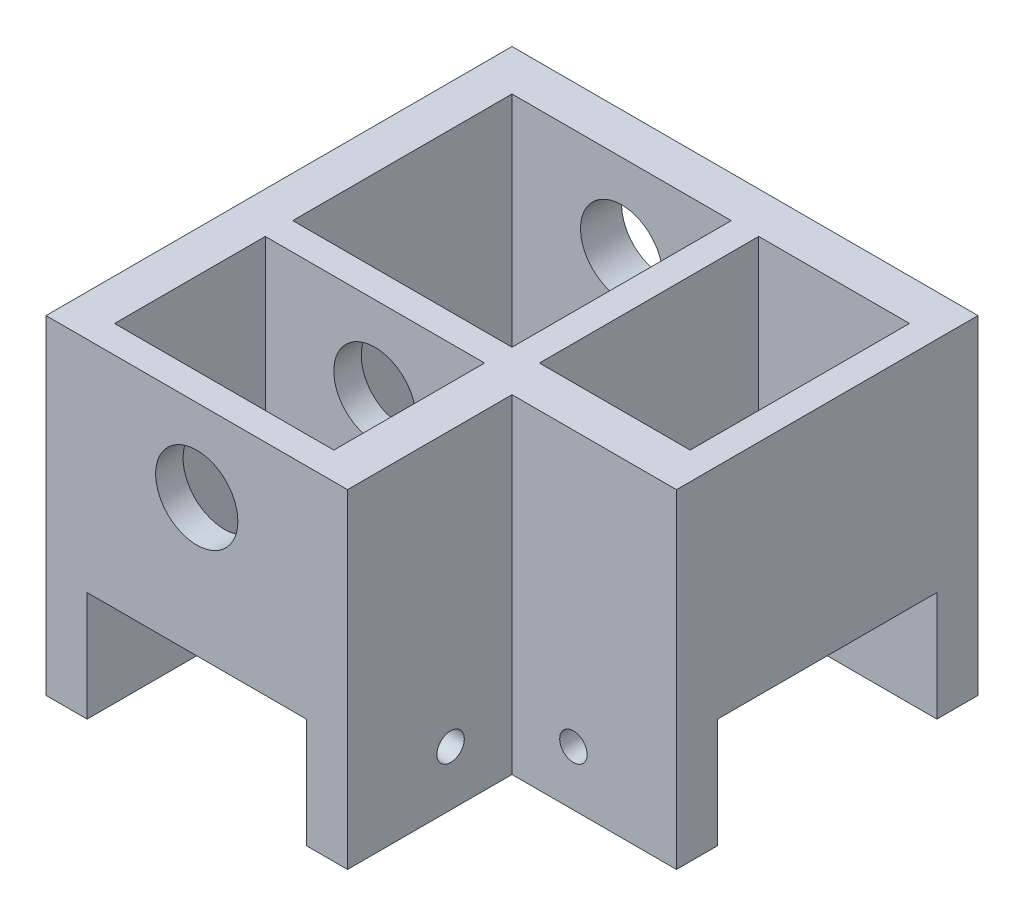
SolidWorks part; units mm, degrees
ref_plane "Front Plane" through (0, 0, 0) normal (0, 0, 1) x (1, 0, 0)
ref_plane "Top Plane" through (0, 0, 0) normal (0, 1, 0) x (1, 0, 0)
ref_plane "Right Plane" through (0, 0, 0) normal (1, 0, 0) x (0, 0, -1)
sketch "Sketch1" plane through (0, 0, 0) normal (0, 1, 0) x (1, 0, 0)
  line L1 (-50.8, -50.8) -> (50.8, -50.8)
  line L2 (-50.8, -50.8) -> (-50.8, 50.8)
  line L3 (-50.8, 50.8) -> (50.8, 50.8)
  line L4 (50.8, -50.8) -> (50.8, 50.8)
  line L5 (-50.8, -50.8) -> (50.8, 50.8) construction
  line L6 (-50.8, 50.8) -> (50.8, -50.8) construction
  point P0 (0, 0)
  dimension "D1" = 101.6
  dimension "D2" = 101.6
extrude "Extrude-Thin1" add sketch "Sketch1" along normal blind 152.4 thin
sketch "Sketch2" plane through (0, 152.4, 0) normal (0, 1, 0) x (1, 0, 0)
  line L0 (-69.85, -69.85) -> (69.85, -69.85) construction
  line L1 (-50.8, -50.8) -> (50.8, -50.8)
  line L2 (-50.8, -50.8) -> (-50.8, -69.85)
  line L3 (-50.8, -69.85) -> (50.8, -69.85)
  line L4 (50.8, -50.8) -> (50.8, -69.85)
ref_plane "Plane1" through (0, 50.8, 0) normal (0, 1, 0) x (1, 0, 0)
sketch "Sketch3" plane through (0, 0, 0) normal (0, -1, 0) x (1, 0, 0)
  line L0 (-69.85, -69.85) -> (-69.85, 69.85) construction
  line L1 (-50.8, 50.8) -> (-69.85, 50.8)
  line L2 (-50.8, 50.8) -> (-50.8, -50.8)
  line L3 (-50.8, -50.8) -> (-69.85, -50.8)
  line L4 (-69.85, 50.8) -> (-69.85, -50.8)
extrude "Cut-Extrude2" cut sketch "Sketch3" against normal up to surface (50.8 mm away)
ref_plane "Plane2" through (72.39, 0, 0) normal (1, 0, 0) x (0, 0, -1)
sketch "Sketch5" plane through (-69.85, 0, 0) normal (-1, 0, 0) x (0, 0, 1)
  line L8 (-50.8, 50.8) -> (50.8, 50.8)
  line L9 (50.8, 50.8) -> (50.8, 0)
  line L10 (50.8, 0) -> (69.85, 0)
  line L11 (69.85, 0) -> (69.85, 152.4)
  line L12 (69.85, 152.4) -> (-69.85, 152.4)
  line L13 (-69.85, 152.4) -> (-69.85, 0)
  line L14 (-69.85, 0) -> (-50.8, 0)
  line L15 (-50.8, 0) -> (-50.8, 50.8)
  line L16 (-50.8, 50.8) -> (50.8, 50.8)
  line L17 (50.8, 50.8) -> (50.8, 0)
  line L18 (50.8, 0) -> (69.85, 0)
  line L19 (69.85, 0) -> (69.85, 152.4)
  line L20 (69.85, 152.4) -> (-69.85, 152.4)
  line L21 (-69.85, 152.4) -> (-69.85, 0)
  line L22 (-69.85, 0) -> (-50.8, 0)
  line L23 (-50.8, 0) -> (-50.8, 50.8)
  dimension "D1" = 0
extrude "Boss-Extrude2" add sketch "Sketch5" along normal blind 76.2
ref_plane "Plane3" through (0, 0, 0) normal (-0.7071, 0, -0.7071) x (-0.7071, 0, 0.7071)
sketch "Sketch6" plane through (0, 152.4, 0) normal (0, 1, 0) x (1, 0, 0)
  line L0 (-50.8, 50.8) -> (-50.8, -50.8) construction
  line L1 (-133.35, 50.8) -> (-63.5, 50.8)
  line L2 (-133.35, 50.8) -> (-133.35, -50.8)
  line L3 (-133.35, -50.8) -> (-63.5, -50.8)
  line L4 (-63.5, 50.8) -> (-63.5, -50.8)
  line L5 (-146.05, -69.85) -> (-146.05, 69.85) construction
  line L6 (50.8, 50.8) -> (-50.8, 50.8) construction
  line L7 (-50.8, -50.8) -> (50.8, -50.8) construction
  dimension "D1" = 12.7
  dimension "D2" = 12.7
extrude "Cut-Extrude3" cut sketch "Sketch6" against normal through all
sketch "Sketch8" plane through (0, 0, 69.85) normal (0, 0, 1) x (1, 0, 0)
  line L0 (-146.05, 0) -> (-146.05, 50.8) construction
  line L1 (-146.05, 0) -> (-146.05, 152.4) construction
  line L2 (-146.05, 25.4) -> (-98.298, 25.4) construction
  circle A0 centre (-98.298, 25.4) radius 6.35
  dimension "D3" = 12.7
  dimension "D1" = 50.8
  dimension "D2" = 47.752
extrude "Cut-Extrude4" cut sketch "Sketch8" against normal through all
mirror "Mirror3" about plane through (0, 0, 0) normal (-0.7071, 0, -0.7071) of "Cut-Extrude3", "Boss-Extrude2", "Cut-Extrude2", "Cut-Extrude4"
mirror "Mirror5" about plane through (72.39, 0, 0) normal (1, 0, 0) of bodies 111
sketch "Sketch9" plane through (72.39, 0, 0) normal (1, 0, 0) x (0, 0, -1)
  line L1 (-146.05, 152.4) -> (69.85, 152.4)
  line L2 (-146.05, 152.4) -> (-146.05, 0)
  line L3 (-146.05, 0) -> (69.85, 0)
  line L4 (69.85, 152.4) -> (69.85, 0)
extrude "Cut-Extrude5" cut sketch "Sketch9" against normal through all
sketch "Sketch11" plane through (0, 0, 63.5) normal (0, 0, 1) x (1, 0, 0)
  line L0 (144.78, 50.8) -> (144.78, 114.3) construction
  line L2 (195.58, 50.8) -> (93.98, 50.8) construction
  circle A0 centre (144.78, 114.3) radius 19.05
  dimension "D2" = 38.1
  dimension "D1" = 63.5
extrude "Cut-Extrude6" cut sketch "Sketch11" against normal through all both and the other way through all
